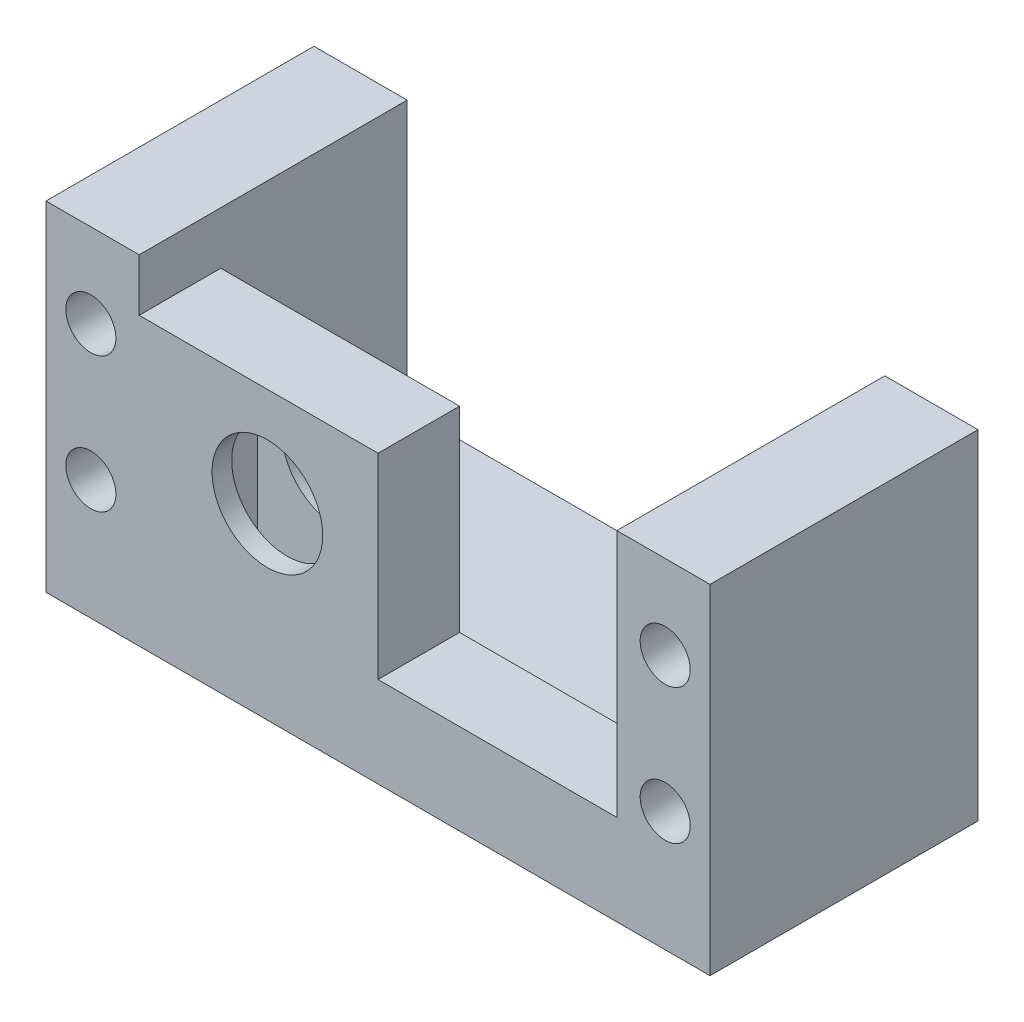
SolidWorks part; units mm, degrees
ref_plane "Спереди" through (0, 0, 0) normal (0, 0, 1) x (1, 0, 0)
ref_plane "Сверху" through (0, 0, 0) normal (0, 1, 0) x (1, 0, 0)
ref_plane "Справа" through (0, 0, 0) normal (1, 0, 0) x (0, 0, -1)
sketch "Эскиз1" plane through (0, 0, 0) normal (0, 0, 1) x (1, 0, 0)
  line L2 (-59.1906, -40.1769) -> (-59.1906, -15.0857)
  line L3 (-59.1906, -15.0857) -> (-51.1906, -15.0857)
  line L4 (-2.1906, -38.0857) -> (-2.1906, -15.0857)
  line L8 (-2.1906, -15.0857) -> (-10.1906, -15.0857)
  line L9 (-10.1906, -15.0857) -> (-10.1906, -38.0857)
  line L10 (-51.1906, -15.0857) -> (-51.1906, -38.0857)
  line L11 (-51.1906, -38.0857) -> (-10.1906, -38.0857)
  line L12 (-59.1906, -40.1769) -> (-59.1906, -44.1769)
  line L13 (-59.1906, -44.1769) -> (-2.1906, -44.1769)
  line L14 (-2.1906, -44.1769) -> (-2.1906, -38.0857)
  point P0 (0, 0)
extrude "Бобышка-Вытянуть1" add sketch "Эскиз1" along normal blind 23
sketch "Эскиз3" plane through (-59.1906, 0, 0) normal (-1, 0, 0) x (0, 0, 1)
  line L5 (0, -15.0857) -> (0, -44.1769) construction
  line L6 (15, -15.0857) -> (0, -15.0857) construction
  line L7 (15, -15.0857) -> (15, -38.2478) construction
  line L8 (15, -38.2478) -> (0, -38.2478) construction
  line L9 (0, -15.0857) -> (0, -38.2478) construction
sketch "Эскиз5" plane through (0, 0, 23) normal (0, 0, 1) x (1, 0, 0)
  line L0 (-51.1906, -38.0857) -> (-51.1906, -15.0857) construction
  line L1 (-10.1906, -28.0857) -> (-24.1906, -28.0857) construction
  line L6 (-30.6906, -18.0857) -> (-30.6906, -34.9839) construction
  line L11 (-51.1906, -28.0857) -> (-37.1906, -28.0857) construction
  line L12 (-10.1906, -38.0857) -> (-51.1906, -38.0857) construction
  line L13 (-10.1906, -38.0857) -> (-10.1906, -18.0857) construction
  line L14 (-10.1906, -18.0857) -> (-51.1906, -18.0857) construction
  line L15 (-51.1906, -38.0857) -> (-51.1906, -18.0857) construction
  line L16 (-21.1906, -34.9839) -> (-51.1906, -34.9839) construction
  line L18 (-21.1906, -19.5857) -> (-51.1906, -19.5857)
  line L19 (-51.1906, -34.9839) -> (-51.1906, -19.5857)
  line L20 (-21.1906, -19.5857) -> (-10.1906, -19.5857)
  line L22 (-21.1906, -34.9839) -> (-10.1906, -34.9839) construction
  line L23 (-10.1906, -19.5857) -> (-10.1906, -34.9839)
  line L24 (-10.1906, -38.0857) -> (-51.1906, -38.0857)
  line L25 (-51.1906, -38.0857) -> (-51.1906, -34.9839)
  line L26 (-10.1906, -38.0857) -> (-10.1906, -34.9839)
  circle A5 centre (-21.1906, -28.0857) radius 2.7
  circle A6 centre (-40.1906, -28.0857) radius 4.75
extrude "Бобышка-Вытянуть6" add sketch "Эскиз5" against normal blind 7
sketch "Эскиз6" plane through (0, 0, 23) normal (0, 0, 1) x (1, 0, 0)
  line L0 (-51.1906, -19.5857) -> (-51.1906, -15.0857) construction
  line L3 (-10.1906, -18.0857) -> (-51.1906, -18.0857)
  line L4 (-51.1906, -38.0857) -> (-51.1906, -18.0857)
  line L5 (-2.1906, -38.0857) -> (-59.1906, -38.0857) construction
  line L6 (-2.1906, -44.1769) -> (-2.1906, -15.0857) construction
  line L7 (-6.0406, -38.0857) -> (-6.0406, -29.5857) construction
  line L8 (-59.1906, -15.0857) -> (-59.1906, -44.1769) construction
  line L9 (-10.1906, -18.0857) -> (-2.1906, -18.0857) construction
  line L10 (-6.0406, -18.0857) -> (-6.0406, -26.5857) construction
  line L11 (-6.0406, -22.2857) -> (-10.1906, -22.2857) construction
  line L12 (-30.6906, -38.0857) -> (-30.6906, -18.0857) construction
  line L13 (-10.1906, -18.0857) -> (-10.1906, -38.0857) construction
  line L14 (-6.0406, -33.8857) -> (-10.1906, -33.8857) construction
  circle A1 centre (-6.0406, -33.8857) radius 2.15
  circle A3 centre (-6.0406, -22.2857) radius 2.15
  circle A4 centre (-55.3406, -22.2857) radius 2.15
  circle A5 centre (-55.3406, -33.8857) radius 2.15
extrude "Вырез-Вытянуть2" cut sketch "Эскиз6" against normal through all contours A1 | A3 | A5 | A4
sketch "Эскиз8" plane through (0, 0, 23) normal (0, 0, 1) x (1, 0, 0)
  line L1 (-10.1906, -19.5857) -> (-30.6906, -19.5857)
  line L2 (-10.1906, -19.5857) -> (-10.1906, -36.4088)
  line L3 (-10.1906, -36.4088) -> (-30.6906, -36.4088)
  line L4 (-30.6906, -19.5857) -> (-30.6906, -36.4088)
extrude "Вырез-Вытянуть4" cut sketch "Эскиз8" against normal up to surface (7 mm away) up to face at (-44.9406, -28.0857, 16)
sketch "Эскиз16" plane through (0, 0, 23) normal (0, 0, 1) x (1, 0, 0)
  line L0 (-40.1906, -21.4357) -> (-40.1906, -34.7357)
  line L1 (-40.1906, -21.4357) -> (-43.9534, -21.4357) construction
  line L2 (-43.9534, -21.4357) -> (-43.9534, -44.1769) construction
  line L3 (-59.1906, -44.1769) -> (-2.1906, -44.1769) construction
  line L4 (-40.1906, -28.0857) -> (-40.1906, -44.1769) construction
  line L5 (-40.1906, -44.1769) -> (-39.0508, -41.093) construction
  point P4 (-40.1906, -28.0857)
sketch "Эскиз14" plane through (0, -44.1769, 0) normal (0, -1, 0) x (-1, 0, 0)
  line L0 (40.2278, -23) -> (40.2278, -19.1629) construction
  line L1 (59.1906, -23) -> (2.1906, -23) construction
  line L3 (33.4278, -21.3129) -> (47.0278, -21.3129)
  line L4 (33.4278, -21.3129) -> (33.4278, -17.0129)
  line L5 (33.4278, -17.0129) -> (47.0278, -17.0129)
  line L6 (47.0278, -21.3129) -> (47.0278, -17.0129)
  line L7 (33.4278, -21.3129) -> (47.0278, -17.0129) construction
  line L8 (33.4278, -17.0129) -> (47.0278, -21.3129) construction
  point P8 (0, 0)
  point P9 (0, 0)
  point P10 (0, 0)
  point P11 (0, 0)
  point P12 (0, 0)
  point P13 (0, 0)
  point P14 (0, 0)
extrude "Вырез-Вытянуть7" cut sketch "Эскиз14" against normal blind 22.74
